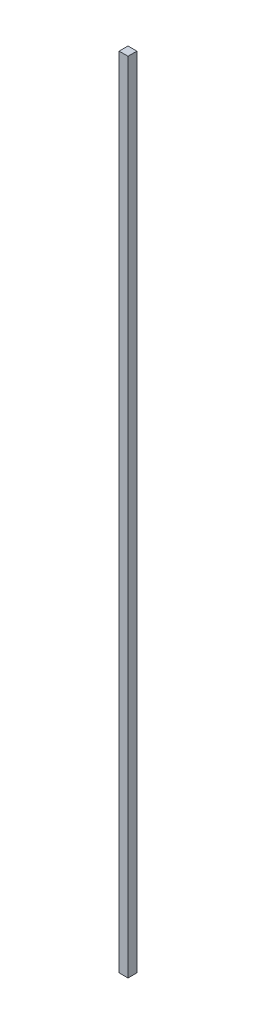
SolidWorks part; units mm, degrees
ref_plane "Front Plane" through (0, 0, 0) normal (0, 0, 1) x (1, 0, 0)
ref_plane "Top Plane" through (0, 0, 0) normal (0, 1, 0) x (1, 0, 0)
ref_plane "Right Plane" through (0, 0, 0) normal (1, 0, 0) x (0, 0, -1)
sketch "Sketch1" plane through (0, 0, 0) normal (0, 1, 0) x (1, 0, 0)
  line L1 (0, 0) -> (25.4, 0)
  line L2 (0, 0) -> (0, -25.4)
  line L3 (0, -25.4) -> (25.4, -25.4)
  line L4 (25.4, 0) -> (25.4, -25.4)
  dimension "D1" = 25.4
  dimension "D2" = 25.4
extrude "Boss-Extrude1" add sketch "Sketch1" along normal blind 2286 contours L1 L4 L3 L2
